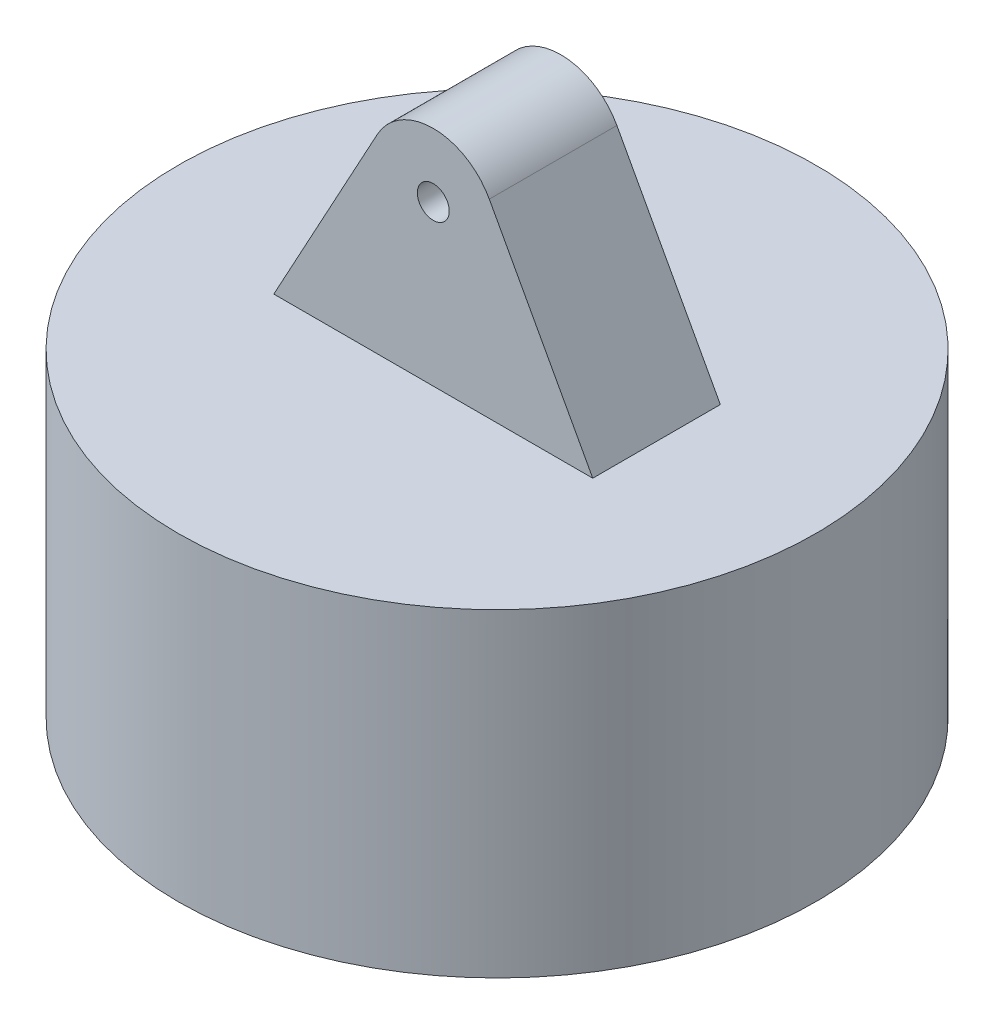
SolidWorks part; units mm, degrees
ref_plane "Front Plane" through (0, 0, 0) normal (0, 0, 1) x (1, 0, 0)
ref_plane "Top Plane" through (0, 0, 0) normal (0, 1, 0) x (1, 0, 0)
ref_plane "Right Plane" through (0, 0, 0) normal (1, 0, 0) x (0, 0, -1)
sketch "Sketch1" plane through (0, 0, 0) normal (0, 0, 1) x (1, 0, 0)
  line L0 (7.493, 0) -> (12.7, 0)
  line L1 (12.7, 0) -> (12.7, 12.7)
  line L2 (12.7, 12.7) -> (0, 12.7)
  line L3 (0, 12.7) -> (0, 7.493)
  circle A0 centre (0, 0) radius 7.493 construction
  arc A1 (0, 7.493) -> (7.493, 0) centre (0, 0) cw
  dimension "D1" = 14.986
  dimension "D2" = 12.7
  dimension "D3" = 12.7
revolve "Revolve1" add sketch "Sketch1" angle 360 about L3
sketch "Sketch2" plane through (0, 0, 0) normal (0, 0, 1) x (1, 0, 0)
  line L0 (-2.2307, 20.2647) -> (-6.35, 12.7)
  line L1 (12.7, 12.7) -> (-12.7, 12.7) construction
  line L2 (2.2307, 20.2647) -> (6.35, 12.7)
  line L3 (-6.35, 12.7) -> (6.35, 12.7)
  line L4 (0, 19.05) -> (0, 12.7) construction
  circle A0 centre (0, 19.05) radius 0.635
  arc A1 (-2.2307, 20.2647) -> (2.2307, 20.2647) centre (0, 19.05) cw
  dimension "D2" = 2.54
  dimension "D3" = 1.27
  dimension "D1" = 6.35
  dimension "D4" = 12.7
extrude "Boss-Extrude1" add sketch "Sketch2" along normal mid plane 5.08
